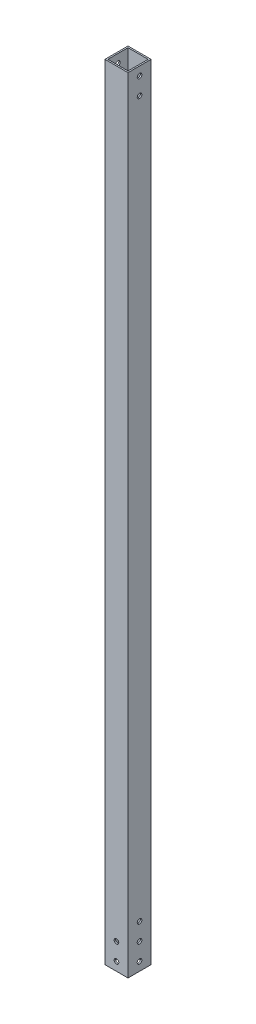
SolidWorks part; units mm, degrees
material "6061-T6 (SS)"
ref_plane "Front Plane" through (0, 0, 0) normal (0, 0, 1) x (1, 0, 0)
ref_plane "Top Plane" through (0, 0, 0) normal (0, 1, 0) x (1, 0, 0)
ref_plane "Right Plane" through (0, 0, 0) normal (1, 0, 0) x (0, 0, -1)
sketch "Sketch1" plane through (0, 0, 0) normal (0, 1, 0) x (1, 0, 0)
  line L0 (11.1125, 11.1125) -> (-11.1125, 11.1125)
  line L1 (12.7, -12.7) -> (-12.7, -12.7)
  line L2 (12.7, -12.7) -> (12.7, 12.7)
  line L3 (12.7, 12.7) -> (-12.7, 12.7)
  line L4 (-12.7, -12.7) -> (-12.7, 12.7)
  line L5 (12.7, -12.7) -> (-12.7, 12.7) construction
  line L6 (12.7, 12.7) -> (-12.7, -12.7) construction
  line L7 (-11.1125, -11.1125) -> (-11.1125, 11.1125)
  line L8 (11.1125, -11.1125) -> (-11.1125, -11.1125)
  line L9 (11.1125, -11.1125) -> (11.1125, 11.1125)
  point P0 (0, 0)
  dimension "D1" = 25.4
  dimension "D2" = 1.5875
extrude "Boss-Extrude1" add sketch "Sketch1" along normal blind 863.6
sketch "Sketch2" plane through (0, 0, 12.7) normal (0, 0, 1) x (1, 0, 0)
  line L0 (-12.7, 0) -> (12.7, 0) construction
  circle A0 centre (0, 9.525) radius 2.5527
  circle A1 centre (0, 28.575) radius 2.5527
  point P7 (0, 0)
  dimension "D1" = 9.525
  dimension "D2" = 19.05
  dimension "D3" = 5.1054
extrude "Cut-Extrude1" cut sketch "Sketch2" against normal through all
sketch "Sketch3" plane through (12.7, 0, 0) normal (1, 0, 0) x (0, 0, -1)
  line L0 (-12.7, 0) -> (12.7, 0) construction
  line L1 (-12.7, 863.6) -> (12.7, 863.6) construction
  circle A0 centre (0, 9.525) radius 2.5527
  circle A1 centre (0, 28.575) radius 2.5527
  circle A2 centre (0, 47.625) radius 2.5527
  circle A3 centre (0, 854.075) radius 2.5527
  circle A4 centre (0, 835.025) radius 2.5527
  point P9 (0, 0)
  dimension "D1" = 9.525
  dimension "D2" = 19.05
  dimension "D3" = 19.05
  dimension "D4" = 5.1054
  dimension "D5" = 9.525
  dimension "D6" = 19.05
extrude "Cut-Extrude2" cut sketch "Sketch3" against normal through all
